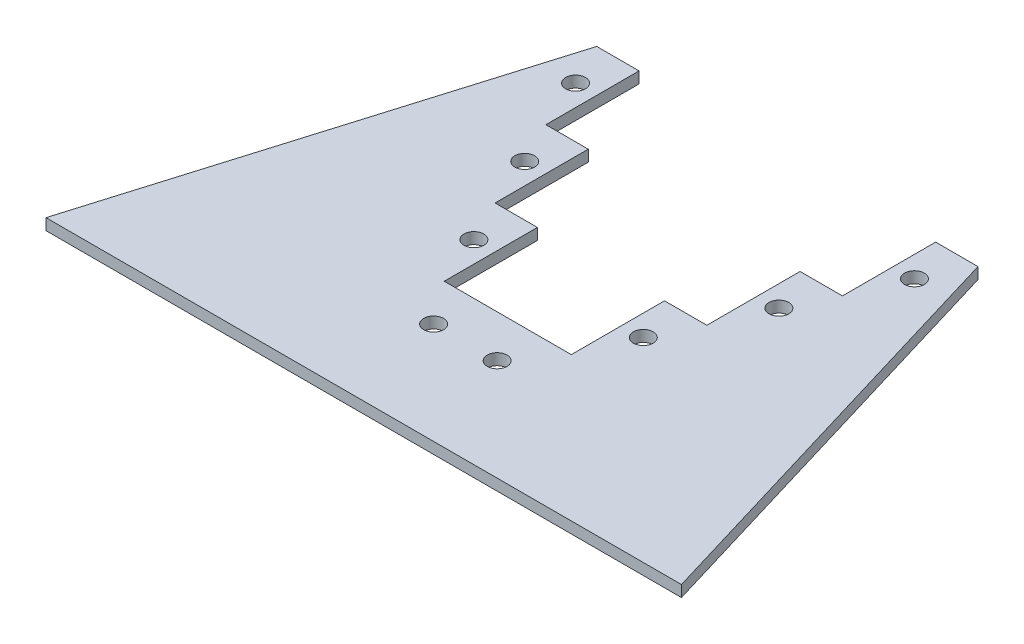
SolidWorks part; units mm, degrees
ref_plane "Front Plane" through (0, 0, 0) normal (0, 0, 1) x (1, 0, 0)
ref_plane "Top Plane" through (0, 0, 0) normal (0, 1, 0) x (1, 0, 0)
ref_plane "Right Plane" through (0, 0, 0) normal (1, 0, 0) x (0, 0, -1)
sketch "Sketch1" plane through (0, 0, 0) normal (0, 1, 0) x (1, 0, 0)
  line L0 (-120, 150) -> (-120, 117)
  line L1 (0, 0) -> (-135, 0)
  line L3 (0, 150) -> (-135, 150)
  line L5 (-120, 117) -> (-105, 117)
  line L6 (-105, 117) -> (-105, 84)
  line L7 (-105, 84) -> (-90, 84)
  line L8 (-90, 84) -> (-90, 51)
  line L9 (-90, 51) -> (-45, 51)
  line L10 (-45, 51) -> (-45, 84)
  line L11 (-45, 84) -> (-30, 84)
  line L12 (-30, 84) -> (-30, 117)
  line L13 (-30, 117) -> (-15, 117)
  line L14 (-15, 117) -> (-15, 150)
  line L15 (-135, 0) -> (-180, 0)
  line L16 (-180, 0) -> (-135, 150)
  line L17 (0, 0) -> (45, 0)
  line L18 (45, 0) -> (0, 150)
  dimension "D1" = 135
  dimension "D2" = 15
  dimension "D3" = 15
  dimension "D4" = 33
  dimension "D5" = 15
  dimension "D6" = 15
  dimension "D7" = 15
  dimension "D8" = 15
  dimension "D9" = 33
  dimension "D10" = 33
  dimension "D11" = 33
  dimension "D12" = 33
  dimension "D13" = 150
  dimension "D14" = 225
  dimension "D15" = 45
  dimension "D16" = 150
  dimension "D17" = 103.4456
extrude "Boss-Extrude2" add sketch "Sketch1" along normal blind 4 contours L17 L18 L3 L14 L13 L12 L11 L10 L9 L8 L7 L6 L5 L0 L16 L15 L1
sketch "Sketch2" plane through (0, 4, 0) normal (0, 1, 0) x (1, 0, 0)
  line L0 (-120, 150) -> (-135, 150) construction
  line L1 (-120, 150) -> (-120, 117) construction
  line L2 (-120, 117) -> (-105, 117) construction
  line L3 (-105, 117) -> (-105, 84) construction
  line L4 (-67.5, 51) -> (-67.5, 0) construction
  line L5 (-90, 51) -> (-45, 51) construction
  line L6 (-180, 0) -> (45, 0) construction
  line L7 (-105, 84) -> (-90, 84) construction
  line L8 (-90, 84) -> (-90, 51) construction
  line L9 (-90, 51) -> (-90, 0) construction
  line L10 (-45, 51) -> (-45, 0) construction
  circle A0 centre (-127.5, 135) radius 3.5
  circle A1 centre (-112.5, 102) radius 3.5
  circle A2 centre (-97.5, 69) radius 3.5
  circle A3 centre (-78.75, 36) radius 3.5
  circle A4 centre (-56.25, 36) radius 3.5
  circle A5 centre (-37.5, 69) radius 3.5
  circle A6 centre (-22.5, 102) radius 3.5
  circle A7 centre (-7.5, 135) radius 3.5
  dimension "D1" = 7
  dimension "D2" = 15
  dimension "D3" = 7.5
  dimension "D4" = 7
  dimension "D5" = 15
  dimension "D7" = 7
  dimension "D8" = 15
  dimension "D10" = 7
  dimension "D11" = 11.25
  dimension "D6" = 7.5
  dimension "D9" = 7.5
  dimension "D12" = 15
extrude "Cut-Extrude1" cut sketch "Sketch2" against normal blind 4
sketch "Sketch3" plane through (0, 4, 0) normal (0, 1, 0) x (1, 0, 0)
  line L1 (-180, 0) -> (45, 0)
  line L2 (-180, 0) -> (-180, -150)
  line L3 (-180, -150) -> (45, -150)
  line L4 (45, 0) -> (45, -150)
  dimension "D1" = 150
  dimension "D2" = 225
extrude "Boss-Extrude3" add sketch "Sketch3" against normal blind 4
